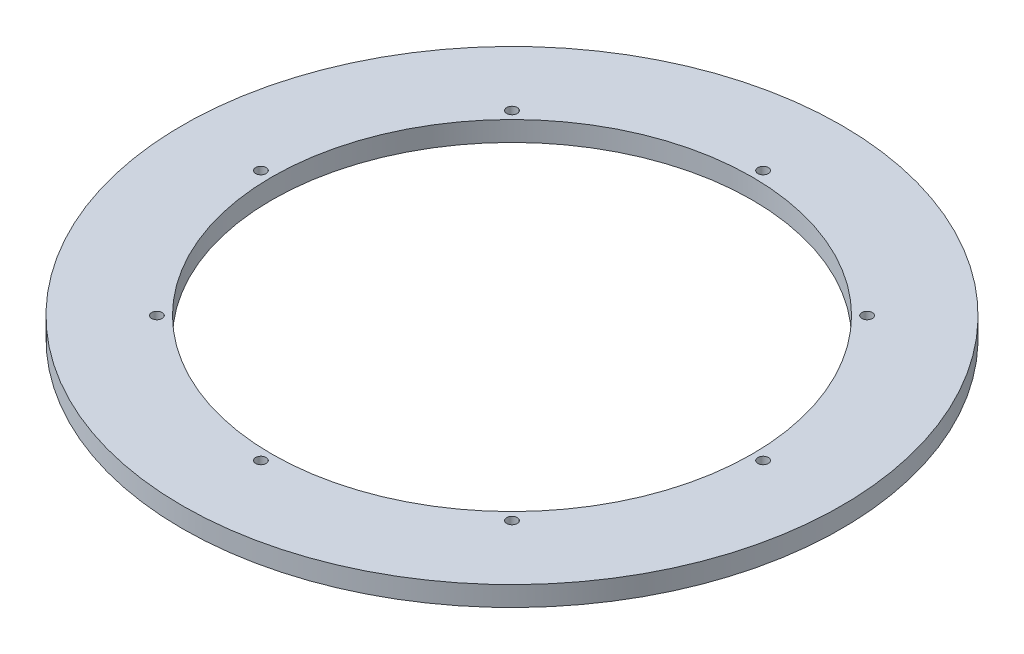
SolidWorks part; units mm, degrees
ref_plane "Front Plane" through (0, 0, 0) normal (0, 0, 1) x (1, 0, 0)
ref_plane "Top Plane" through (0, 0, 0) normal (0, 1, 0) x (1, 0, 0)
ref_plane "Right Plane" through (0, 0, 0) normal (1, 0, 0) x (0, 0, -1)
sketch "Sketch1" plane through (0, 0, 0) normal (1, 0, 0) x (0, 0, -1)
  line L0 (0, -6970.8867) -> (0, 342324.5874) construction
  line L2 (-315, -8.7794) -> (-229.5, -8.7794)
  line L3 (-315, -8.7794) -> (-315, -27.7794)
  line L4 (-315, -27.7794) -> (-229.5, -27.7794)
  line L5 (-229.5, -8.7794) -> (-229.5, -27.7794)
  line L6 (-315, -8.7794) -> (-229.5, -27.7794) construction
  line L7 (-315, -27.7794) -> (-229.5, -8.7794) construction
  point P1 (-272.25, -18.2794)
  dimension "D1" = 85.5
  dimension "D2" = 459
  dimension "D3" = 19
revolve "Revolve1" add sketch "Sketch1" angle 360 about L0
sketch "Sketch2" plane through (0, -8.7794, 0) normal (0, 1, 0) x (1, 0, 0)
  line L0 (0, -1000) -> (0, 49000) construction
  circle A0 centre (0, 240) radius 5
  circle A1 centre (169.7056, 169.7056) radius 5
  circle A2 centre (240, 0) radius 5
  circle A3 centre (169.7056, -169.7056) radius 5
  circle A4 centre (0, -240) radius 5
  circle A5 centre (-169.7056, -169.7056) radius 5
  circle A6 centre (-240, 0) radius 5
  circle A7 centre (-169.7056, 169.7056) radius 5
  point P22 (0, 0)
  dimension "D1" = 240
  dimension "D2" = 10
  dimension "D3" = 8
extrude "Cut-Extrude1" cut sketch "Sketch2" against normal through all
